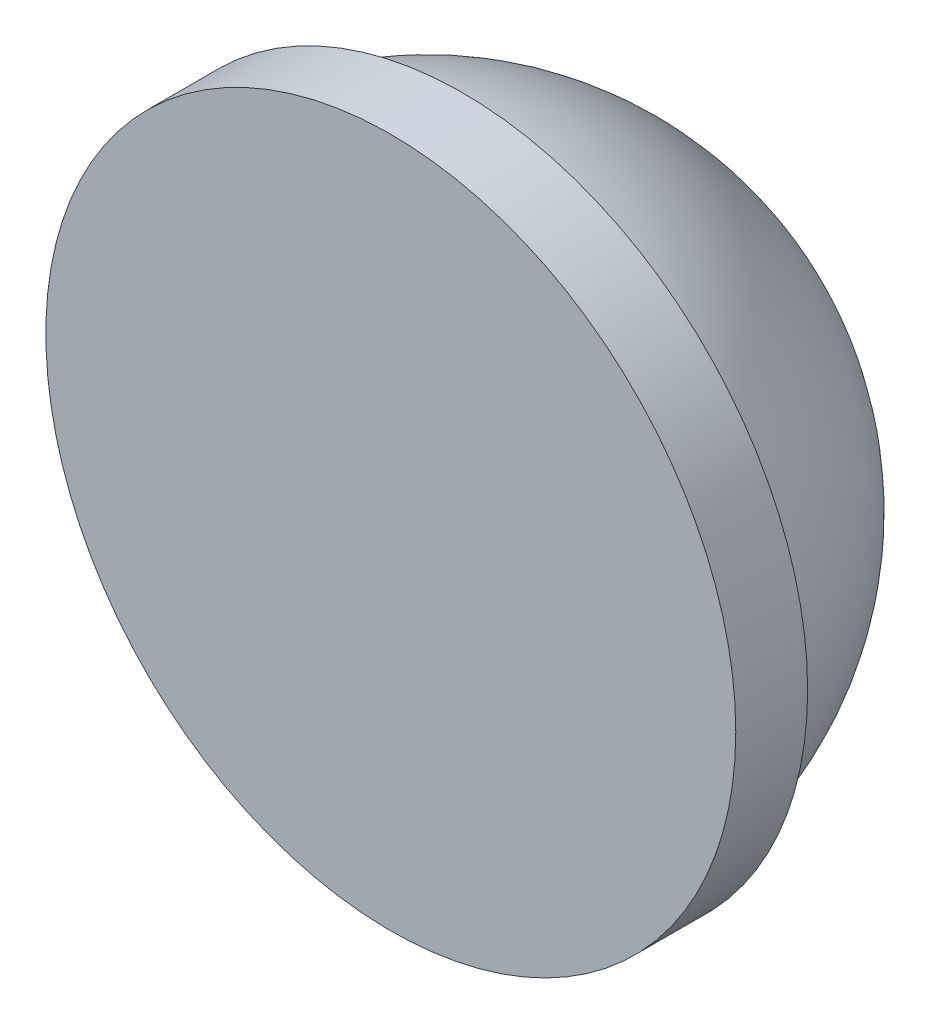
SolidWorks part; units mm, degrees
ref_plane "Plan de face" through (0, 0, 0) normal (0, 0, 1) x (1, 0, 0)
ref_plane "Plan de dessus" through (0, 0, 0) normal (0, 1, 0) x (1, 0, 0)
ref_plane "Plan de droite" through (0, 0, 0) normal (1, 0, 0) x (0, 0, -1)
sketch "Esquisse2" plane through (0, 0, 0) normal (1, 0, 0) x (0, 0, -1)
  line L0 (-0.5, 0) -> (4.5, 0)
  line L3 (0.5, 4.8) -> (-0.5, 4.8)
  line L6 (0.5, 4.8) -> (0, 0) construction
  line L7 (-0.5, 0) -> (-0.5, 4.8)
  line L9 (0, 0) -> (-0.5, 4.8) construction
  line L10 (0.5, 4.4721) -> (0.5, 4.8)
  arc A1 (4.5, 0) -> (0.5, 4.4721) centre (0, 0) ccw
  point P0 (0, 0)
  dimension "D2" = 1
revolve "Révolution1" add sketch "Esquisse2" angle 360 about L0
